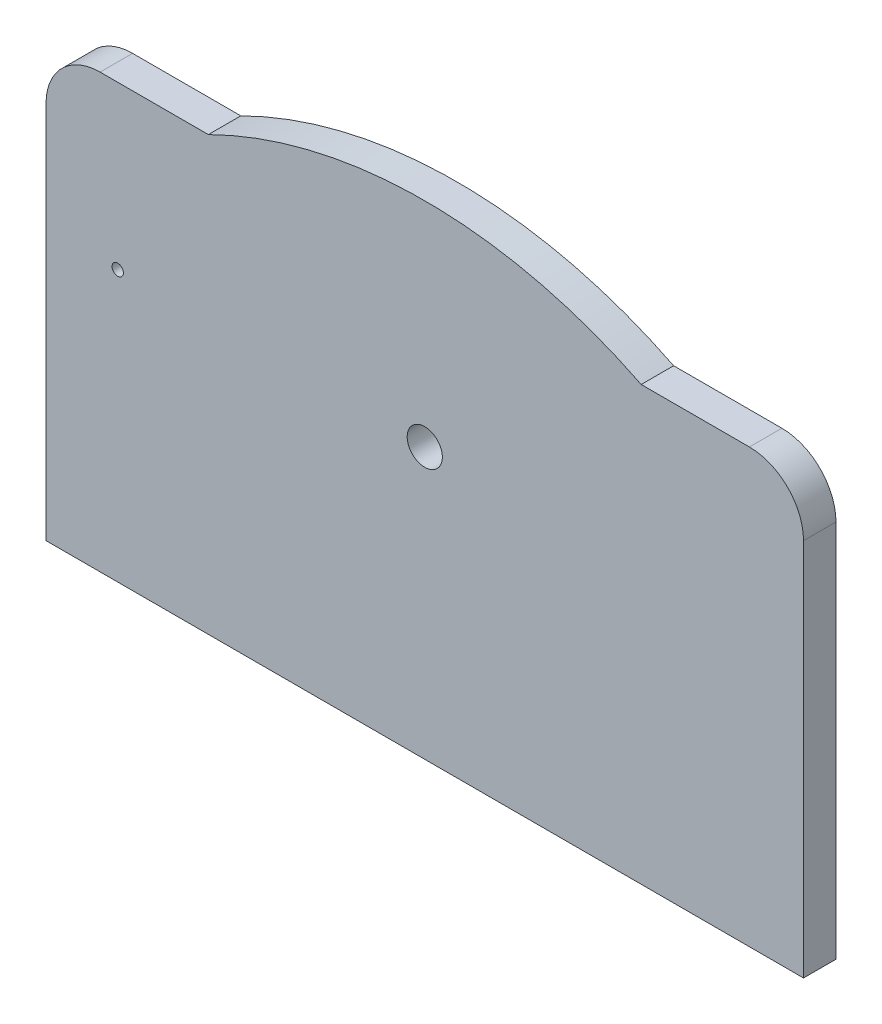
SolidWorks part; units mm, degrees
ref_plane "Plan de face" through (0, 0, 0) normal (0, 0, 1) x (1, 0, 0)
ref_plane "Plan de dessus" through (0, 0, 0) normal (0, 1, 0) x (1, 0, 0)
ref_plane "Plan de droite" through (0, 0, 0) normal (1, 0, 0) x (0, 0, -1)
sketch "Esquisse1" plane through (0, 0, 0) normal (0, 0, 1) x (1, 0, 0)
  line L1 (-60, 40) -> (80, 40)
  line L2 (-60, 40) -> (-60, -40)
  line L3 (-60, -40) -> (80, -40)
  line L4 (80, 40) -> (80, -40)
  dimension "D1" = 140
  dimension "D2" = 80
extrude "Extrusion1" add sketch "Esquisse1" along normal blind 6
fillet "Congé1" radius 10 2 edges at (-60, 40, 3) (80, 40, 3)
sketch "Esquisse2" plane through (0, 0, 6) normal (0, 0, 1) x (1, 0, 0)
  line L0 (70, 40) -> (-50, 40) construction
  line L1 (80, -40) -> (80, 30) construction
  line L2 (-60, 30) -> (-60, -40) construction
  circle A0 centre (10, 10) radius 3.25
  point P2 (10, 40)
  dimension "D1" = 6.5
  dimension "D2" = 30
  dimension "D3" = 70
  dimension "D4" = 70
extrude "Enlèv. mat.-Extru.1" cut sketch "Esquisse2" against normal through all
sketch "Esquisse5" plane through (0, 0, 0) normal (0, 0, -1) x (-1, 0, 0)
  circle A0 centre (19.77, 14.8) radius 1.05
  circle A1 centre (19.77, 5.3) radius 1.05
  circle A2 centre (-10, 10) radius 3.25 construction
  dimension "D3" = 2.1
  dimension "D4" = 2.1
  dimension "D5" = 4.8
  dimension "D1" = 29.77
  dimension "D2" = 29.77
  dimension "D6" = 4.7
extrude "Enlèv. mat.-Extru.2" cut sketch "Esquisse5" against normal blind 1
sketch "Esquisse6" plane through (0, 0, 0) normal (0, 0, -1) x (-1, 0, 0)
  line L0 (-70, 40) -> (50, 40) construction
  line L1 (-50, 40) -> (30, 40)
  arc A0 (30, 40) -> (-50, 40) centre (-10, -40.2367) ccw
extrude "Extrusion2" add sketch "Esquisse6" against normal up to vertex (6 mm away)
sketch "Esquisse7" plane through (0, 0, 0) normal (0, 0, -1) x (-1, 0, 0)
  line L0 (60, 30) -> (60, -40) construction
  line L1 (30, 40) -> (50, 40) construction
  circle A0 centre (46.75, 10) radius 1.05
  dimension "D1" = 2.1
  dimension "D2" = 13.25
  dimension "D3" = 30
extrude "Enlèv. mat.-Extru.3" cut sketch "Esquisse7" against normal through all
